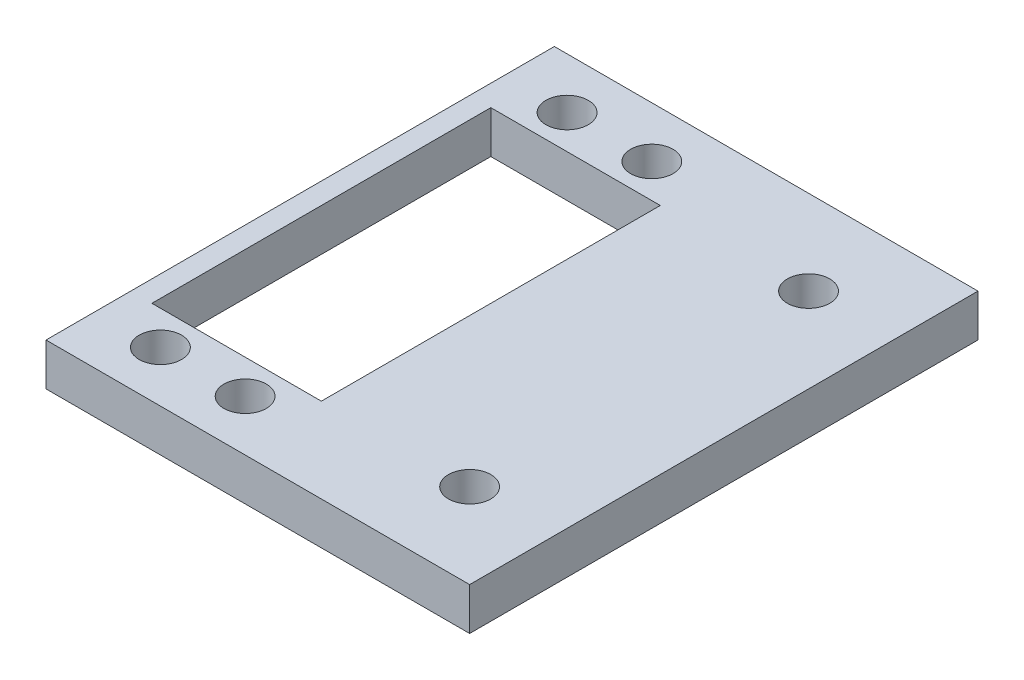
SolidWorks part; units mm, degrees
ref_plane "Front Plane" through (0, 0, 0) normal (0, 0, 1) x (1, 0, 0)
ref_plane "Top Plane" through (0, 0, 0) normal (0, 1, 0) x (1, 0, 0)
ref_plane "Right Plane" through (0, 0, 0) normal (1, 0, 0) x (0, 0, -1)
sketch "Sketch1" plane through (0, 0, 0) normal (0, 1, 0) x (1, 0, 0)
  line L0 (-25.6195, 41.9912) -> (-25.6195, -18.0088) construction
  line L1 (-50.6195, 41.9912) -> (-0.6195, 41.9912)
  line L2 (-50.6195, 41.9912) -> (-50.6195, -18.0088)
  line L3 (-50.6195, -18.0088) -> (-0.6195, -18.0088)
  line L4 (-0.6195, 41.9912) -> (-0.6195, -18.0088)
  line L5 (-20.6195, 41.9912) -> (-20.6195, -18.0088) construction
  line L6 (-20.6195, 11.9912) -> (-0.6195, 11.9912) construction
  line L7 (-10.6195, 10.3264) -> (-10.6195, -33.119) construction
  line L8 (-50.6195, 11.9912) -> (-25.6195, 11.9912) construction
  line L9 (-38.1195, 1.9912) -> (-38.1195, -18.0088) construction
  line L11 (-48.1195, 31.9912) -> (-28.1195, 31.9912)
  line L12 (-48.1195, 31.9912) -> (-48.1195, -8.0088)
  line L13 (-48.1195, -8.0088) -> (-28.1195, -8.0088)
  line L14 (-28.1195, 31.9912) -> (-28.1195, -8.0088)
  line L15 (-48.1195, 31.9912) -> (-28.1195, -8.0088) construction
  line L16 (-48.1195, -8.0088) -> (-28.1195, 31.9912) construction
  circle A0 centre (-10.6195, 31.9912) radius 2.5
  circle A1 centre (-10.6195, -8.0088) radius 2.5
  circle A2 centre (-43.1195, 35.9912) radius 2.5
  circle A3 centre (-33.1195, 35.9912) radius 2.5
  circle A4 centre (-43.1195, -12.0088) radius 2.5
  circle A5 centre (-33.1195, -12.0088) radius 2.5
  point P19 (-38.1195, 11.9912)
  dimension "D4" = 5
  dimension "D5" = 20
  dimension "D1" = 50
  dimension "D2" = 60
  dimension "D3" = 20
  dimension "D6" = 40
  dimension "D7" = 20
extrude "Boss-Extrude1" add sketch "Sketch1" along normal blind 5
